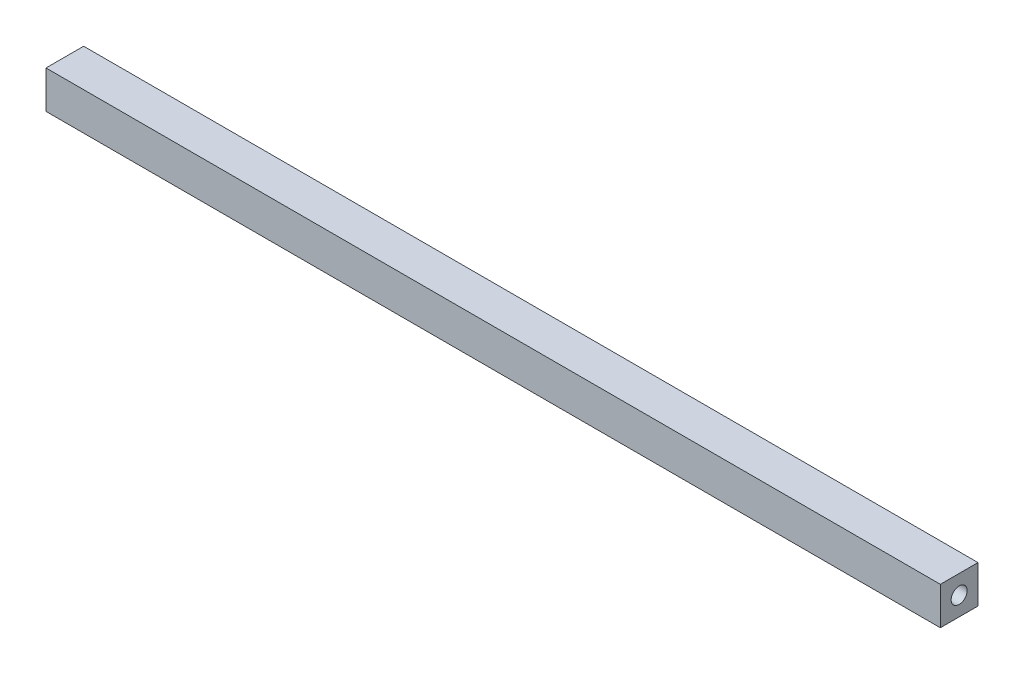
SolidWorks part; units mm, degrees
ref_plane "Plano frontal" through (0, 0, 0) normal (0, 0, 1) x (1, 0, 0)
ref_plane "Plano superior" through (0, 0, 0) normal (0, 1, 0) x (1, 0, 0)
ref_plane "Plano direito" through (0, 0, 0) normal (1, 0, 0) x (0, 0, -1)
sketch "Esboço1" plane through (0, 0, 0) normal (1, 0, 0) x (0, 0, -1)
  line L1 (-2, -2) -> (2, -2)
  line L2 (-2, -2) -> (-2, 2)
  line L3 (-2, 2) -> (2, 2)
  line L4 (2, -2) -> (2, 2)
  line L5 (-2, -2) -> (2, 2) construction
  line L6 (-2, 2) -> (2, -2) construction
  point P0 (0, 0)
  dimension "D1" = 4
extrude "Ressalto-extrusão1" add sketch "Esboço1" along normal mid plane 95
sketch "Esboço2" plane through (47.5, 0, 0) normal (1, 0, 0) x (0, 0, -1)
  circle A0 centre (0, 0) radius 0.85
  dimension "D1" = 1.7
extrude "Corte-extrusão1" cut sketch "Esboço2" against normal up to next and the other way through all
